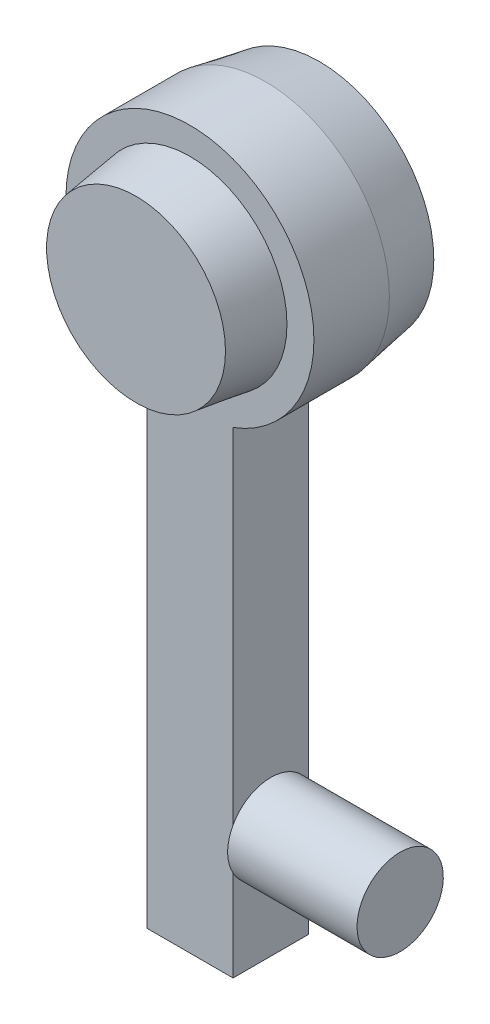
SolidWorks part; units mm, degrees
ref_plane "Ön Düzlem" through (0, 0, 0) normal (0, 0, 1) x (1, 0, 0)
ref_plane "Üst Düzlem" through (0, 0, 0) normal (0, 1, 0) x (1, 0, 0)
ref_plane "Sağ Düzlem" through (0, 0, 0) normal (1, 0, 0) x (0, 0, -1)
sketch "Sketch1" plane through (0, 0, 0) normal (0, 0, 1) x (1, 0, 0)
  line L0 (0, 0) -> (0, -55) construction
  line L2 (-4, -10.7819) -> (-4, -55)
  line L3 (-4, -55) -> (4, -55)
  line L4 (4, -10.7819) -> (4, -55)
  arc A0 (4, -10.7819) -> (-4, -10.7819) centre (0, 0) ccw
  dimension "D2" = 11.5
  dimension "D1" = 8
  dimension "D3" = 55
extrude "Boss-Extrude1" add sketch "Sketch1" against normal blind 7
sketch "Sketch2" plane through (0, 0, 0) normal (0, 0, 1) x (1, 0, 0)
  circle A0 centre (0, 0) radius 9
  dimension "D1" = 18
extrude "Boss-Extrude2" add sketch "Sketch2" along normal blind 5 draft 8 contours A0
sketch "Sketch4" plane through (0, 0, -7) normal (0, 0, -1) x (-1, 0, 0)
  circle A0 centre (0, 0) radius 11.5
  arc A1 (4, -10.7819) -> (-4, -10.7819) centre (0, 0) ccw construction
extrude "Boss-Extrude3" add sketch "Sketch4" along normal blind 5 draft 10
sketch "Sketch5" plane through (4, 0, 0) normal (1, 0, 0) x (0, 0, -1)
  line L0 (7, -55) -> (0, -55) construction
  circle A0 centre (3.5, -44.64) radius 4
  point P5 (3.5, -55)
  dimension "D1" = 8
  dimension "D2" = 10.36
extrude "Boss-Extrude4" add sketch "Sketch5" along normal blind 12
sketch "Sketch6" plane through (0, 0, -12) normal (0, 0, -1) x (-1, 0, 0)
  circle A0 centre (0, 0) radius 9
  dimension "D1" = 18
extrude "Cut-Extrude1" cut sketch "Sketch6" against normal up to surface (5 mm away) up to face at (1.3333, -36.927, -7)
sketch "Sketch7" plane through (0, 0, -7) normal (0, 0, -1) x (-1, 0, 0)
  circle A0 centre (0, 0) radius 9
  circle A2 centre (0, 0) radius 9 construction
extrude "Cut-Extrude3" cut sketch "Sketch7" along normal up to surface (5 mm away) draft 10
